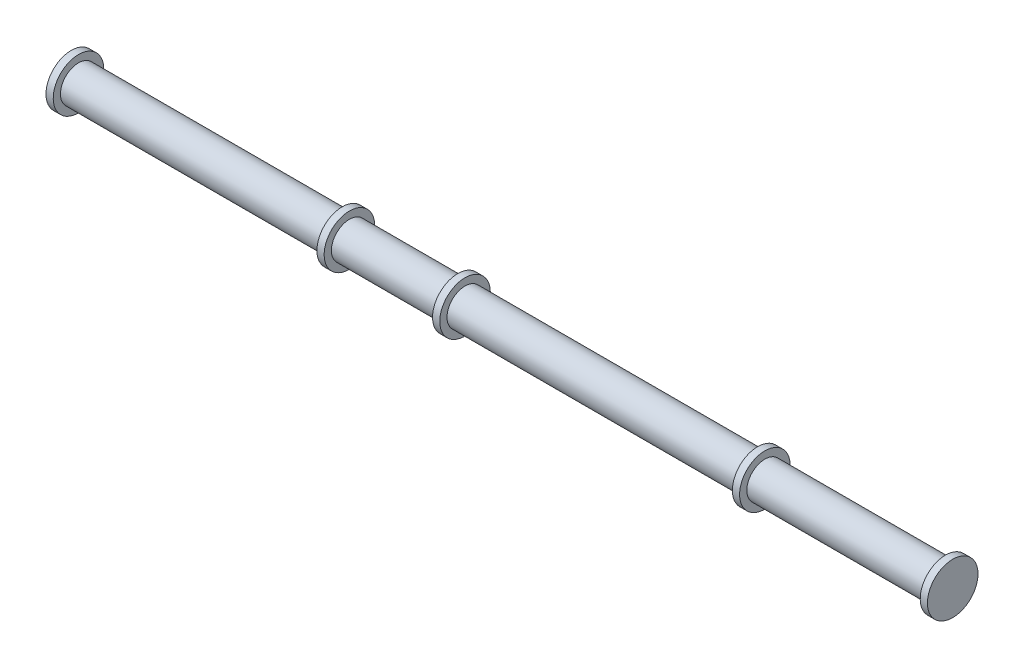
SolidWorks part; units mm, degrees
material "6061 Alloy"
ref_plane "Front Plane" through (0, 0, 0) normal (0, 0, 1) x (1, 0, 0)
ref_plane "Top Plane" through (0, 0, 0) normal (0, 1, 0) x (1, 0, 0)
ref_plane "Right Plane" through (0, 0, 0) normal (1, 0, 0) x (0, 0, -1)
sketch "Sketch2" plane through (0, 0, 0) normal (0, 0, 1) x (1, 0, 0)
  line L0 (0, 0) -> (0, 7)
  line L1 (0, 7) -> (2, 7)
  line L2 (2, 7) -> (2, 5)
  line L3 (2, 5) -> (32, 5)
  line L4 (32, 5) -> (75, 5)
  line L5 (75, 5) -> (75, 7)
  line L6 (75, 7) -> (77, 7)
  line L7 (77, 7) -> (77, 5)
  line L8 (77, 5) -> (107, 5)
  line L9 (107, 5) -> (107, 7)
  line L10 (107, 7) -> (109, 7)
  line L11 (109, 7) -> (109, 5)
  line L12 (109, 5) -> (190, 5)
  line L13 (190, 5) -> (190, 7)
  line L14 (190, 7) -> (192, 7)
  line L15 (192, 7) -> (192, 5)
  line L16 (192, 5) -> (242, 5)
  line L17 (242, 5) -> (242, 7)
  line L18 (242, 7) -> (244, 7)
  line L19 (244, 7) -> (244, 5)
  line L20 (244, 5) -> (244, 0)
  line L21 (244, 0) -> (0, 0)
  dimension "D1" = 7
  dimension "D2" = 2
  dimension "D3" = 2
  dimension "D4" = 30
  dimension "D5" = 43
  dimension "D6" = 2
  dimension "D7" = 2
  dimension "D8" = 2
  dimension "D9" = 30
  dimension "D10" = 2
  dimension "D11" = 2
  dimension "D12" = 2
  dimension "D13" = 50
  dimension "D14" = 81
  dimension "D15" = 2
  dimension "D16" = 2
  dimension "D17" = 2
  dimension "D18" = 2
  dimension "D19" = 2
  dimension "D20" = 2
revolve "Revolve1" add sketch "Sketch2" angle 360 about L21
